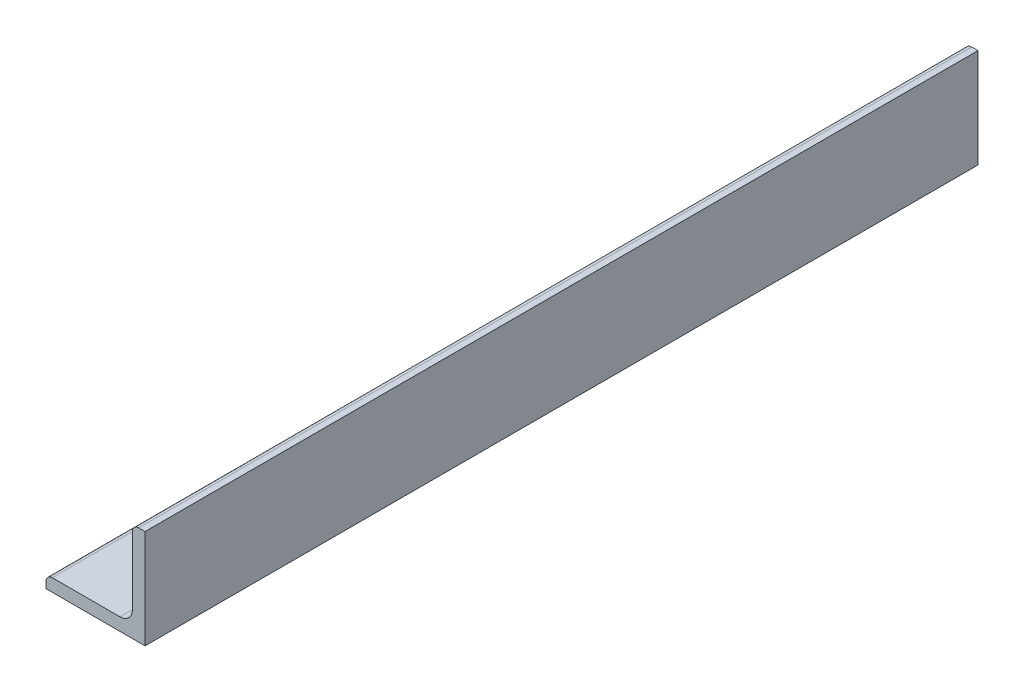
SolidWorks part; units mm, degrees
material "Plain Carbon Steel"
ref_plane "Front Plane" through (0, 0, 0) normal (0, 0, 1) x (1, 0, 0)
ref_plane "Top Plane" through (0, 0, 0) normal (0, 1, 0) x (1, 0, 0)
ref_plane "Right Plane" through (0, 0, 0) normal (1, 0, 0) x (0, 0, -1)
sketch "Sketch0" plane through (0, 0, 0) normal (0, 0, 1) x (1, 0, 0)
  line L0 (-12.7, -12.7) -> (12.7, -12.7)
  line L1 (12.7, -12.7) -> (12.7, 12.7)
  line L2 (12.7, 0) -> (0, 0) construction
  line L3 (0, 0) -> (0, -12.7) construction
  line L4 (9.45, -6.275) -> (9.45, 12.7) construction
  line L5 (6.275, -9.45) -> (-12.7, -9.45) construction
  arc A0 (9.45, -6.275) -> (6.275, -9.45) centre (6.275, -6.275) cw
  point P3 (8.5201, -8.5201)
  dimension "Inside Corner Radius" = 3.175
  dimension "Outside Height" = 25.4
  dimension "Inside Height" = 22.15
  dimension "Inside Width" = 22.15
  dimension "Outside Width" = 25.4
  dimension "D1" = 3.25
  dimension "D2" = 3.25
sketch "Sketch1" plane through (0, 0, 0) normal (1, 0, 0) x (0, 0, -1)
  line L0 (152.4, 0) -> (-152.4, 0)
  point P4 (0, 0)
  dimension "Length" = 304.8
sketch "Sketch2" plane through (0, 0, 0) normal (0, 0, 1) x (1, 0, 0)
  line L0 (-12.7, -12.7) -> (12.7, -12.7)
  line L1 (12.7, -12.7) -> (12.7, 12.7)
  line L2 (12.7, 12.7) -> (9.45, 12.7) construction
  line L3 (9.45, 11.075) -> (9.45, -6.275)
  line L4 (6.275, -9.45) -> (-11.075, -9.45)
  line L5 (-12.7, -12.7) -> (-12.7, -9.45) construction
  line L6 (11.075, 12.7) -> (12.7, 12.7)
  line L7 (-12.7, -11.075) -> (-12.7, -12.7)
  line L8 (12.7, 0) -> (0, 0) construction
  line L9 (0, 0) -> (0, -12.7) construction
  arc A0 (9.45, 11.075) -> (11.075, 12.7) centre (11.075, 11.075) cw
  arc A1 (-12.7, -11.075) -> (-11.075, -9.45) centre (-11.075, -11.075) cw
  arc A2 (9.45, -6.275) -> (6.275, -9.45) centre (6.275, -6.275) cw
  dimension "Inside Radius" = 3.175
  dimension "Height" = 25.4
  dimension "Width" = 25.4
  dimension "Thickness" = 3.25
extrude "Boss-Extrude1" add sketch "Sketch2" along normal mid plane 304.8
sketch "Break Locations" plane through (0, 0, 0) normal (1, 0, 0) x (0, 0, -1)
  line L0 (-126.492, 0) -> (126.492, 0)
  line L1 (-152.4, -12.7) -> (-152.4, 12.7) construction
  line L2 (152.4, -12.7) -> (152.4, 12.7) construction
  point P0 (-130.81, 0)
  point P1 (130.81, 0)
  point P10 (0, 0)
  point P11 (126.492, 0)
  point P13 (-126.492, 0)
  dimension "D1" = 21.59
  dimension "D2" = 21.59
  dimension "D3" = 25.908
sketch "Sketch3" plane through (0, 0, -152.4) normal (0, 0, -1) x (-1, 0, 0)
  line L6 (12.7, -12.7) -> (12.7, -11.075)
  line L7 (11.075, -9.45) -> (-6.275, -9.45)
  line L8 (-9.45, -6.275) -> (-9.45, 11.075)
  line L9 (-11.075, 12.7) -> (-12.7, 12.7)
  line L10 (-12.7, 12.7) -> (-12.7, -12.7)
  line L11 (-12.7, -12.7) -> (12.7, -12.7)
  line L12 (12.7, -12.7) -> (12.7, -11.075)
  line L13 (11.075, -9.45) -> (-6.275, -9.45)
  line L14 (-9.45, -6.275) -> (-9.45, 11.075)
  line L15 (-11.075, 12.7) -> (-12.7, 12.7)
  line L16 (-12.7, 12.7) -> (-12.7, -12.7)
  line L17 (-12.7, -12.7) -> (12.7, -12.7)
  arc A3 (12.7, -11.075) -> (11.075, -9.45) centre (11.075, -11.075) ccw
  arc A4 (-9.45, -6.275) -> (-6.275, -9.45) centre (-6.275, -6.275) ccw
  arc A5 (-9.45, 11.075) -> (-11.075, 12.7) centre (-11.075, 11.075) ccw
  arc A6 (12.7, -11.075) -> (11.075, -9.45) centre (11.075, -11.075) ccw
  arc A7 (-9.45, -6.275) -> (-6.275, -9.45) centre (-6.275, -6.275) ccw
  arc A8 (-9.45, 11.075) -> (-11.075, 12.7) centre (-11.075, 11.075) ccw
  dimension "D1" = 0
extrude "Cut-Extrude1" cut sketch "Sketch3" against normal up to surface (6.35 mm away) contours L17 L12 A6 L13 A7 L14 A8 L15 L16
ref_plane "Plane1" through (0, 0, 0) normal (0.7071, -0.7071, 0) x (0, 0, -1)
sketch "Sketch4" plane through (0, 0, 0) normal (0.7071, -0.7071, 0) x (0, 0, -1)
  line L3 (-152.4, -17.9605) -> (146.05, -17.9605) construction
  line L4 (146.05, 17.9605) -> (110.65, 17.9605)
  line L5 (146.05, 17.9605) -> (146.05, -17.9605)
  line L6 (146.05, -17.9605) -> (110.65, -17.9605)
  line L7 (110.65, 17.9605) -> (110.65, -17.9605)
  dimension "D1" = 35.4
extrude "Cut-Extrude2" cut sketch "Sketch4" against normal through all both and the other way through all
sketch "Sketch5" plane through (12.7, 0, 0) normal (1, 0, 0) x (0, 0, -1)
  line L1 (-152.4, -12.7) -> (-102.95, -12.7)
  line L2 (-152.4, -12.7) -> (-152.4, 12.7)
  line L3 (-152.4, 12.7) -> (-102.95, 12.7)
  line L4 (-102.95, -12.7) -> (-102.95, 12.7)
  dimension "D1" = 49.45
extrude "Cut-Extrude3" cut sketch "Sketch5" against normal through all
equation "\"D1@Break Locations\" = .85 * \"Height@Sketch2\""
equation "\"D2@Break Locations\"=\"D1@Break Locations\""
equation "\"Height@Sketch2\" = \"Outside Height@Sketch0\""
equation "\"Width@Sketch2\" = \"Outside Width@Sketch0\""
equation "\"Inside Radius@Sketch2\" = \"Inside Corner Radius@Sketch0\""
equation "\"Length@Boss-Extrude1\" = \"Length@Sketch1\""
equation "\"D3@Break Locations\"=\"D2@Break Locations\"*1.2"
